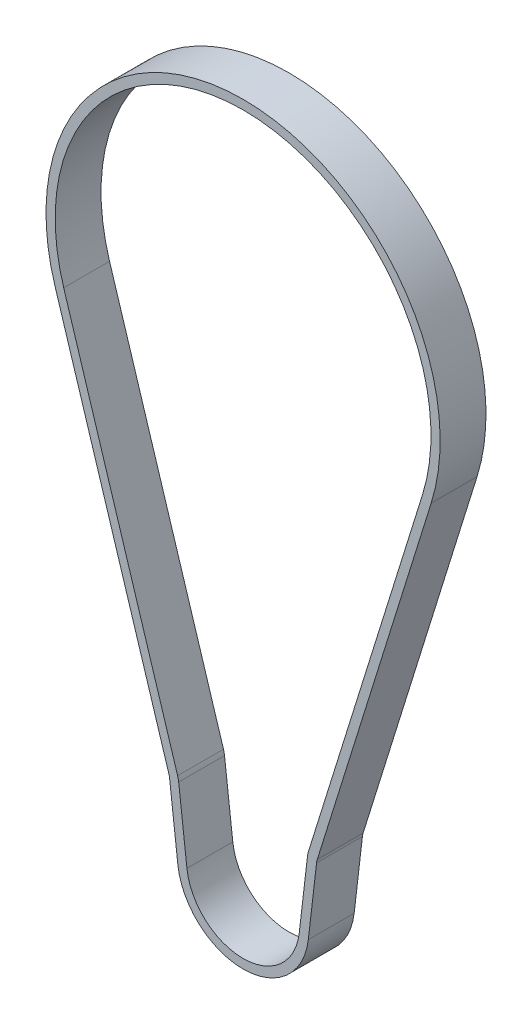
SolidWorks part; units mm, degrees
ref_plane "前视基准面" through (0, 0, 0) normal (0, 0, 1) x (1, 0, 0)
ref_plane "上视基准面" through (0, 0, 0) normal (0, 1, 0) x (1, 0, 0)
ref_plane "右视基准面" through (0, 0, 0) normal (1, 0, 0) x (0, 0, -1)
sketch "草图1" plane through (0, 0, 0) normal (0, 0, 1) x (1, 0, 0)
  line L0 (-14.2282, -1.6623) -> (-16.027, 13.7342)
  line L1 (14.2282, -1.6623) -> (16.027, 13.7342)
  line L2 (-20, 13.27) -> (20, 13.27) construction
  line L3 (-16.1812, 14.4601) -> (-41.024, 94.1751)
  line L4 (16.1812, 14.4601) -> (41.024, 94.1751)
  line L5 (-14.2717, 15.0552) -> (-39.1145, 94.7701)
  line L6 (14.2717, 15.0552) -> (39.1145, 94.7701)
  line L7 (12.2417, -1.4302) -> (14.0405, 13.9663)
  line L8 (-12.2417, -1.4302) -> (-14.0405, 13.9663)
  arc A0 (-14.2282, -1.6623) -> (14.2282, -1.6623) centre (0, 0) ccw
  arc A1 (41.024, 94.1751) -> (-41.024, 94.1751) centre (0, 106.96) ccw
  arc A2 (-16.027, 13.7342) -> (-16.1812, 14.4601) centre (-20, 13.27) ccw
  arc A3 (16.1812, 14.4601) -> (16.027, 13.7342) centre (20, 13.27) ccw
  arc A4 (-14.0405, 13.9663) -> (-14.2717, 15.0552) centre (-20, 13.27) ccw
  arc A5 (39.1145, 94.7701) -> (-39.1145, 94.7701) centre (0, 106.96) ccw
  arc A6 (14.2717, 15.0552) -> (14.0405, 13.9663) centre (20, 13.27) ccw
  arc A7 (-12.2417, -1.4302) -> (12.2417, -1.4302) centre (0, 0) ccw
  point P11 (0, 13.27)
  dimension "D1" = 40
  dimension "D2" = 8
  dimension "D3" = 28.65
  dimension "D4" = 85.94
  dimension "D5" = 106.96
  dimension "D6" = 13.27
  dimension "D7" = 2
extrude "凸台-拉伸1" add sketch "草图1" along normal mid plane 10
